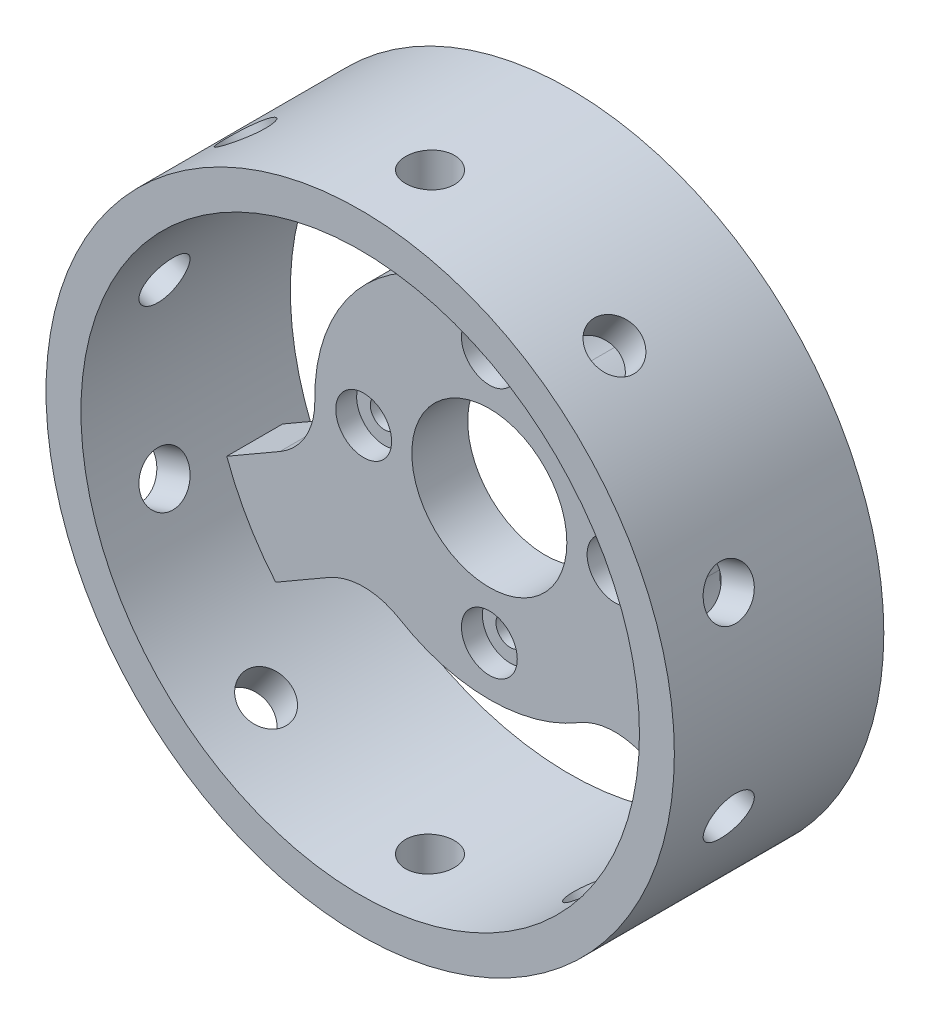
SolidWorks part; units mm, degrees
ref_plane "Front Plane" through (0, 0, 0) normal (0, 0, 1) x (1, 0, 0)
ref_plane "Top Plane" through (0, 0, 0) normal (0, 1, 0) x (1, 0, 0)
ref_plane "Right Plane" through (0, 0, 0) normal (1, 0, 0) x (0, 0, -1)
sketch "Sketch1" plane through (0, 0, 0) normal (0, 0, 1) x (1, 0, 0)
  circle A0 centre (0, 0) radius 45
  dimension "D1" = 90
extrude "Boss-Extrude1" add sketch "Sketch1" along normal blind 30
sketch "Sketch2" plane through (0, 0, 0) normal (0, 0, 1) x (1, 0, 0)
  circle A0 centre (0, 0) radius 40
  dimension "D1" = 80
extrude "Cut-Extrude1" cut sketch "Sketch2" along normal through all both
sketch "Sketch5" plane through (0, 0, 0) normal (0, 0, 1) x (1, 0, 0)
  circle A0 centre (0, 0) radius 25
  dimension "D1" = 50
extrude "Boss-Extrude3" add sketch "Sketch5" along normal blind 8 from offset 3.5
sketch "Sketch6" plane through (0, 0, 0) normal (0, 0, 1) x (1, 0, 0)
  line L0 (0, 0) -> (-73.8626, -42.6446) construction
  line L1 (0, 0) -> (69.4127, -40.0754) construction
  line L2 (0, -16.5) -> (0, 16.5) construction
  line L3 (-7, 24) -> (7, 24)
  line L4 (7, 24) -> (7, 41)
  line L5 (7, 41) -> (-7, 41)
  line L6 (-7, 41) -> (-7, 24)
  line L8 (17.2846, -18.0622) -> (32.007, -26.5622)
  line L9 (32.007, -26.5622) -> (39.007, -14.4378)
  line L10 (39.007, -14.4378) -> (24.2846, -5.9378)
  line L12 (24.2846, -5.9378) -> (17.2846, -18.0622)
  line L14 (-17.2846, -18.0622) -> (-32.007, -26.5622)
  line L15 (-32.007, -26.5622) -> (-39.007, -14.4378)
  line L16 (-39.007, -14.4378) -> (-24.2846, -5.9378)
  line L18 (-24.2846, -5.9378) -> (-17.2846, -18.0622)
  circle A0 centre (0, 0) radius 25 construction
  dimension "D1" = 120
  dimension "D2" = 120
  dimension "D3" = 17
  dimension "D4" = 17
  dimension "D5" = 17
  dimension "D6" = 14
  dimension "D7" = 14
  dimension "D8" = 14
  dimension "D9" = 7
  dimension "D10" = 7
  dimension "D11" = 7
extrude "Boss-Extrude4" add sketch "Sketch6" along normal blind 8 from offset 3.5
sketch "Sketch9" plane through (0, 0, 0) normal (0, 0, 1) x (1, 0, 0)
  circle A0 centre (0, 0) radius 11.1
  dimension "D1" = 22.2
extrude "Cut-Extrude4" cut sketch "Sketch9" along normal through all
sketch "Sketch10" plane through (0, 0, 0) normal (0, 0, 1) x (1, 0, 0)
  line L0 (0, -8.25) -> (0, 8.25) construction
  line L1 (8.25, 0) -> (-8.25, 0) construction
  circle A0 centre (0, 18) radius 2.05
  circle A1 centre (18, 0) radius 2.05
  circle A2 centre (0, -18) radius 2.05
  circle A3 centre (-18, 0) radius 2.05
  dimension "D5" = 4.1
  dimension "D1" = 18
  dimension "D2" = 18
  dimension "D3" = 18
  dimension "D4" = 18
extrude "Cut-Extrude5" cut sketch "Sketch10" along normal through all
sketch "Sketch11" plane through (0, 0, 0) normal (0, 0, 1) x (1, 0, 0)
  circle A0 centre (18, 0) radius 4
  circle A1 centre (0, -18) radius 4
  circle A2 centre (-18, 0) radius 4
  circle A3 centre (0, 18) radius 4
  dimension "D1" = 8
extrude "Cut-Extrude6" cut sketch "Sketch11" against normal blind 3 from surface
fillet "Fillet1" radius 10 6 edges at (-24.2846, -5.9378, 7.5) (-17.2846, -18.0622, 7.5) (17.2846, -18.0622, 7.5) (24.2846, -5.9378, 7.5) (7, 24, 7.5) (-7, 24, 7.5)
sketch "Sketch12" plane through (0, 0, 0) normal (0, 1, 0) x (1, 0, 0)
  line L0 (0, -16.5) -> (0, 16.5) construction
  line L1 (-49.5, 0) -> (49.5, 0) construction
  circle A0 centre (0, -20) radius 3.5
  dimension "D1" = 7
  dimension "D2" = 20
extrude "Cut-Extrude7" cut sketch "Sketch12" against normal through all both and the other way through all
pattern_circular "CirPattern1" count 10 every 36 about axis through (0, 0, 30) along (0, 0, -1) of "Cut-Extrude7"
